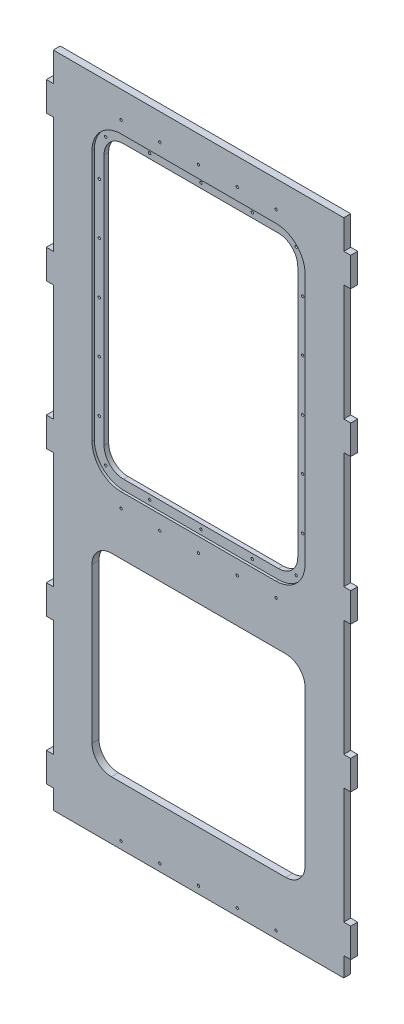
SolidWorks part; units mm, degrees
ref_plane "Front" through (0, 0, 0) normal (0, 0, 1) x (1, 0, 0)
ref_plane "Top" through (0, 0, 0) normal (0, 1, 0) x (1, 0, 0)
ref_plane "Right" through (0, 0, 0) normal (1, 0, 0) x (0, 0, -1)
sketch "Sketch2" plane through (0, 0, 0) normal (0, 0, 1) x (1, 0, 0)
  line L1 (0, 0) -> (381, 0)
  line L2 (0, 0) -> (0, 1727.2)
  line L3 (0, 1727.2) -> (381, 1727.2)
  line L4 (381, 0) -> (381, 1727.2)
  dimension "D1" = 381
  dimension "D2" = 1727.2
extrude "Boss-Extrude1" add sketch "Sketch2" against normal blind 18.288
sketch "Sketch3" plane through (0, 0, 0) normal (0, 0, 1) x (1, 0, 0)
  line L0 (0, 1727.2) -> (0, 0) construction
  line L1 (0, 50.8) -> (-18.288, 50.8)
  line L2 (0, 50.8) -> (0, 127)
  line L3 (0, 127) -> (-18.288, 127)
  line L4 (-18.288, 50.8) -> (-18.288, 127)
  dimension "D1" = 18.288
  dimension "D2" = 76.2
  dimension "D3" = 50.8
extrude "Boss-Extrude2" add sketch "Sketch3" against normal blind 18.288
pattern_linear "LPattern1" count 5 spacing 381 along (0, 1, 0) of "Boss-Extrude2"
mirror "Mirror1" about plane through (381, 0, -18.288) normal (1, 0, 0) of "Boss-Extrude1", "LPattern1", "Boss-Extrude2"
sketch "Sketch4" plane through (0, 0, 0) normal (0, 0, 1) x (1, 0, 0)
  line L0 (127, 1600.2) -> (635, 838.2) construction
  line L1 (177.8, 1600.2) -> (584.2, 1600.2)
  line L2 (127, 1549.4) -> (127, 889)
  line L3 (177.8, 838.2) -> (584.2, 838.2)
  line L4 (635, 1549.4) -> (635, 889)
  line L5 (635, 1600.2) -> (127, 838.2) construction
  line L7 (762, 1727.2) -> (0, 1727.2) construction
  line L96 (762, 1193.8) -> (762, 889) construction
  arc A0 (584.2, 838.2) -> (635, 889) centre (584.2, 889) ccw
  arc A1 (127, 889) -> (177.8, 838.2) centre (177.8, 889) ccw
  arc A2 (177.8, 1600.2) -> (127, 1549.4) centre (177.8, 1549.4) ccw
  arc A3 (584.2, 1600.2) -> (635, 1549.4) centre (584.2, 1549.4) cw
  point P6 (381, 1219.2)
  dimension "D5" = 50.8
  dimension "D1" = 508
  dimension "D2" = 762
  dimension "D4" = 508
  dimension "D6" = 381
extrude "Cut-Extrude2" cut sketch "Sketch4" against normal through all
sketch "Sketch5" plane through (0, 0, 0) normal (0, 0, 1) x (1, 0, 0)
  line L0 (127, 1600.2) -> (635, 838.2) construction
  line L1 (177.8, 1600.2) -> (584.2, 1600.2)
  line L2 (127, 1549.4) -> (127, 889)
  line L3 (177.8, 838.2) -> (584.2, 838.2)
  line L4 (635, 1549.4) -> (635, 889)
  line L5 (635, 1600.2) -> (127, 838.2) construction
  line L6 (762, 1727.2) -> (0, 1727.2) construction
  line L96 (177.8, 1625.6) -> (584.2, 1625.6)
  line L97 (660.4, 1549.4) -> (660.4, 889)
  line L98 (177.8, 812.8) -> (584.2, 812.8)
  line L99 (101.6, 1549.4) -> (101.6, 889)
  arc A0 (584.2, 838.2) -> (635, 889) centre (584.2, 889) ccw
  arc A1 (127, 889) -> (177.8, 838.2) centre (177.8, 889) ccw
  arc A2 (177.8, 1600.2) -> (127, 1549.4) centre (177.8, 1549.4) ccw
  arc A3 (584.2, 1600.2) -> (635, 1549.4) centre (584.2, 1549.4) cw
  arc A4 (584.2, 1625.6) -> (660.4, 1549.4) centre (584.2, 1549.4) cw
  arc A5 (584.2, 812.8) -> (660.4, 889) centre (584.2, 889) ccw
  arc A6 (101.6, 889) -> (177.8, 812.8) centre (177.8, 889) ccw
  arc A7 (177.8, 1625.6) -> (101.6, 1549.4) centre (177.8, 1549.4) ccw
  dimension "D5" = 50.8
  dimension "D1" = 508
  dimension "D2" = 762
  dimension "D3" = 25.4
  dimension "D4" = 101.6
extrude "Cut-Extrude4" cut sketch "Sketch5" against normal blind 6.35
sketch "Sketch7" plane through (0, 0, -6.35) normal (0, 0, 1) x (1, 0, 0)
  line L0 (177.8, 1612.9) -> (584.2, 1612.9) construction
  line L1 (638.0815, 835.1185) -> (123.9185, 1603.2815) construction
  line L2 (638.0815, 1603.2815) -> (123.9185, 835.1185) construction
  line L3 (101.6, 1219.2) -> (660.4, 1219.2) construction
  line L4 (101.6, 1549.4) -> (101.6, 889) construction
  line L5 (660.4, 889) -> (660.4, 1549.4) construction
  line L7 (381, 812.8) -> (381, 1625.6) construction
  line L8 (177.8, 812.8) -> (584.2, 812.8) construction
  line L9 (584.2, 1625.6) -> (177.8, 1625.6) construction
  circle A0 centre (381, 825.5) radius 3.175
  circle A5 centre (515.62, 825.5) radius 3.175
  circle A8 centre (246.38, 825.5) radius 3.175
  circle A11 centre (381, 1612.9) radius 3.175
  circle A21 centre (114.3, 1219.2) radius 3.175
  circle A24 centre (650.24, 825.5) radius 3.175 [skipped]
  circle A25 centre (515.62, 1612.9) radius 3.175
  circle A26 centre (246.38, 1612.9) radius 3.175
  circle A29 centre (114.3, 1353.82) radius 3.175
  circle A30 centre (114.3, 1488.44) radius 3.175
  circle A31 centre (114.3, 949.96) radius 3.175
  circle A32 centre (114.3, 1084.58) radius 3.175
  circle A33 centre (114.3, 1353.82) radius 3.175
  circle A34 centre (114.3, 1488.44) radius 3.175
  circle A35 centre (114.3, 949.96) radius 3.175
  circle A36 centre (114.3, 1084.58) radius 3.175
  circle A37 centre (114.3, 1353.82) radius 3.175
  circle A38 centre (114.3, 1488.44) radius 3.175
  circle A39 centre (114.3, 949.96) radius 3.175
  circle A40 centre (114.3, 1084.58) radius 3.175
  circle A41 centre (114.3, 1353.82) radius 3.175
  circle A42 centre (114.3, 1488.44) radius 3.175
  circle A43 centre (114.3, 949.96) radius 3.175
  circle A44 centre (114.3, 1084.58) radius 3.175
  circle A45 centre (647.7, 1084.58) radius 3.175
  circle A46 centre (647.7, 949.96) radius 3.175
  circle A47 centre (647.7, 1488.44) radius 3.175
  circle A48 centre (647.7, 1353.82) radius 3.175
  circle A49 centre (647.7, 1084.58) radius 3.175
  circle A50 centre (647.7, 949.96) radius 3.175
  circle A51 centre (647.7, 1488.44) radius 3.175
  circle A52 centre (647.7, 1353.82) radius 3.175
  circle A53 centre (647.7, 1084.58) radius 3.175
  circle A54 centre (647.7, 949.96) radius 3.175
  circle A55 centre (647.7, 1488.44) radius 3.175
  circle A56 centre (647.7, 1353.82) radius 3.175
  circle A57 centre (647.7, 1084.58) radius 3.175
  circle A58 centre (647.7, 949.96) radius 3.175
  circle A59 centre (647.7, 1488.44) radius 3.175
  circle A60 centre (647.7, 1353.82) radius 3.175
  circle A61 centre (647.7, 1219.2) radius 3.175
  arc A63 (584.2, 812.8) -> (660.4, 889) centre (584.2, 889) ccw construction
  arc A64 (177.8, 1625.6) -> (101.6, 1549.4) centre (177.8, 1549.4) ccw construction
  arc A65 (660.4, 1549.4) -> (584.2, 1625.6) centre (584.2, 1549.4) ccw construction
  arc A66 (101.6, 889) -> (177.8, 812.8) centre (177.8, 889) ccw construction
  circle A67 centre (131.2664, 1592.3036) radius 3.175
  circle A68 centre (131.2664, 846.0964) radius 3.175
  circle A69 centre (630.7336, 846.0964) radius 3.175
  circle A70 centre (630.7336, 1592.3036) radius 3.175
  dimension "D2" = 3
  dimension "D11" = 12.7
  dimension "D12" = 134.62
  dimension "D7" = 3
extrude "Cut-Extrude6" cut sketch "Sketch7" against normal blind 25.4 contours A30 | A29 | A21 | A32 | A31 | A8 | A0 | A5 | A46 | A45 | A61 | A48 | A47 | A25 | A11 | A26
sketch "Sketch8" plane through (0, 0, 0) normal (0, 0, 1) x (1, 0, 0)
  line L1 (101.6, 660.4) -> (660.4, 660.4)
  line L2 (101.6, 660.4) -> (101.6, 152.4)
  line L3 (101.6, 152.4) -> (660.4, 152.4)
  line L4 (660.4, 660.4) -> (660.4, 152.4)
  dimension "D1" = 558.8
  dimension "D2" = 101.6
  dimension "D3" = 508
  dimension "D4" = 152.4
extrude "Cut-Extrude7" cut sketch "Sketch8" against normal blind 25.4
fillet "Fillet1" radius 50.8 4 edges at (101.6, 152.4, -9.144) (660.4, 152.4, -9.144) (660.4, 660.4, -9.144) (101.6, 660.4, -9.144)
sketch "Sketch10" plane through (0, 0, -6.35) normal (0, 0, 1) x (1, 0, 0)
  line L0 (123.9185, 1603.2815) -> (638.0815, 835.1185) construction
  line L1 (638.0815, 1603.2815) -> (123.9185, 835.1185) construction
  line L2 (381, 1625.6) -> (381, 812.8) construction
  line L3 (584.2, 1625.6) -> (177.8, 1625.6) construction
  line L4 (177.8, 812.8) -> (584.2, 812.8) construction
  line L5 (101.6, 1219.2) -> (660.4, 1219.2) construction
  line L6 (101.6, 1549.4) -> (101.6, 889) construction
  line L7 (660.4, 889) -> (660.4, 1549.4) construction
  arc A0 (177.8, 1625.6) -> (101.6, 1549.4) centre (177.8, 1549.4) ccw construction
  arc A1 (584.2, 812.8) -> (660.4, 889) centre (584.2, 889) ccw construction
  arc A2 (660.4, 1549.4) -> (584.2, 1625.6) centre (584.2, 1549.4) ccw construction
  arc A3 (101.6, 889) -> (177.8, 812.8) centre (177.8, 889) ccw construction
  circle A4 centre (131.2686, 1592.3003) radius 3.175
  arc A5 (177.8, 1600.2) -> (127, 1549.4) centre (177.8, 1549.4) ccw construction
  circle A6 centre (131.2686, 846.0997) radius 3.175
  circle A7 centre (630.7314, 846.0997) radius 3.175
  circle A8 centre (630.7314, 1592.3003) radius 3.175
  point P33 (141.879, 1585.321)
  dimension "D1" = 12.7
extrude "Cut-Extrude8" cut sketch "Sketch10" against normal blind 25.4
sketch "Sketch11" plane through (0, 0, 0) normal (0, 0, 1) x (1, 0, 0)
sketch "Sketch12" plane through (0, 0, -18.288) normal (0, 0, -1) x (-1, 0, 0)
  line L0 (-762, 812.8) -> (-762, 508) construction
  line L1 (-127, 793.75) -> (-635, 793.75) construction
  line L2 (-127, 793.75) -> (-127, 755.65) construction
  line L3 (-127, 755.65) -> (-635, 755.65) construction
  line L4 (-635, 793.75) -> (-635, 755.65) construction
  line L5 (-127, 793.75) -> (-635, 755.65) construction
  line L6 (-127, 755.65) -> (-635, 793.75) construction
  line L7 (0, 0) -> (-762, 0) construction
  line L8 (-127, 38.1) -> (-635, 38.1) construction
  line L9 (-127, 0) -> (-635, 0) construction
  line L10 (-635, 38.1) -> (-635, 0) construction
  line L11 (-127, 38.1) -> (-127, 0) construction
  circle A0 centre (-177.8, 774.7) radius 3.175
  circle A1 centre (-279.4, 774.7) radius 3.175
  circle A2 centre (-381, 774.7) radius 3.175
  circle A3 centre (-482.6, 774.7) radius 3.175
  circle A4 centre (-584.2, 774.7) radius 3.175
  circle A5 centre (-177.8, 19.05) radius 3.175
  circle A6 centre (-279.4, 19.05) radius 3.175
  circle A7 centre (-381, 19.05) radius 3.175
  circle A8 centre (-482.6, 19.05) radius 3.175
  circle A9 centre (-584.2, 19.05) radius 3.175
  point P0 (-381, 774.7)
  dimension "D4" = 6.35
  dimension "D5" = 50.8
  dimension "D1" = 381
  dimension "D2" = 38.1
  dimension "D3" = 508
  dimension "D7" = 774.7
  dimension "D6" = 5
  dimension "D8" = 2
extrude "Cut-Extrude9" cut sketch "Sketch12" against normal through all
sketch "Sketch13" plane through (0, 0, -18.288) normal (0, 0, -1) x (-1, 0, 0)
  circle A0 centre (-584.2, 1657.35) radius 3.175
  circle A1 centre (-482.6, 1657.35) radius 3.175
  circle A2 centre (-381, 1657.35) radius 3.175
  circle A3 centre (-279.4, 1657.35) radius 3.175
  circle A4 centre (-177.8, 1657.35) radius 3.175
  dimension "D1" = 5
extrude "Cut-Extrude10" cut sketch "Sketch13" against normal through all
